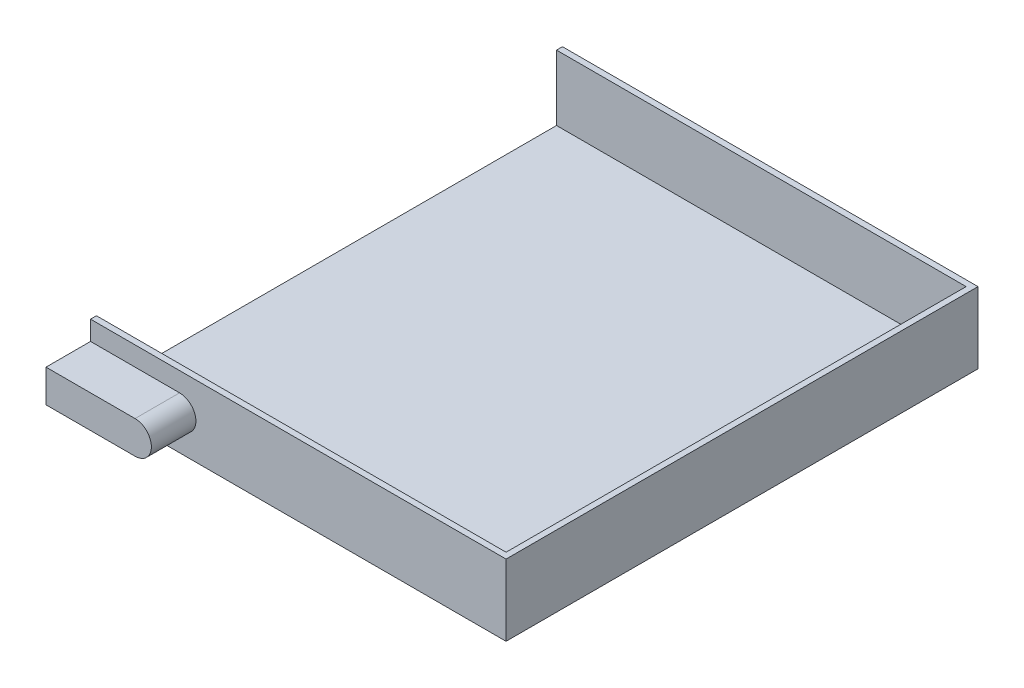
SolidWorks part; units mm, degrees
ref_plane "前视基准面" through (0, 0, 0) normal (0, 0, 1) x (1, 0, 0)
ref_plane "上视基准面" through (0, 0, 0) normal (0, 1, 0) x (1, 0, 0)
ref_plane "右视基准面" through (0, 0, 0) normal (1, 0, 0) x (0, 0, -1)
sketch "草图1" plane through (0, 0, 0) normal (0, 1, 0) x (1, 0, 0)
  line L1 (0, 0) -> (138, 0)
  line L2 (0, 0) -> (0, -155)
  line L3 (0, -155) -> (138, -155)
  line L4 (138, 0) -> (138, -155)
  dimension "D1" = 138
  dimension "D2" = 155
extrude "凸台-拉伸1" add sketch "草图1" along normal blind 22
shell "抽壳1" thickness 2
sketch "草图4" plane through (0, 0, 157) normal (0, 0, 1) x (1, 0, 0)
  line L0 (0, 22) -> (0, -2) construction
  line L1 (30, 10) -> (0, 10) construction
  line L2 (30, 4.5) -> (0, 4.5)
  line L3 (30, 15.5) -> (0, 15.5)
  line L4 (0, 15.5) -> (0, 4.5)
  arc A0 (30, 4.5) -> (30, 15.5) centre (30, 10) ccw
  point P0 (0, 10)
  point P1 (30, 10)
  point P4 (-30, 10)
  point P7 (0, 10)
  dimension "D1" = 30
  dimension "D2" = 30
extrude "凸台-拉伸3" add sketch "草图4" along normal blind 15
